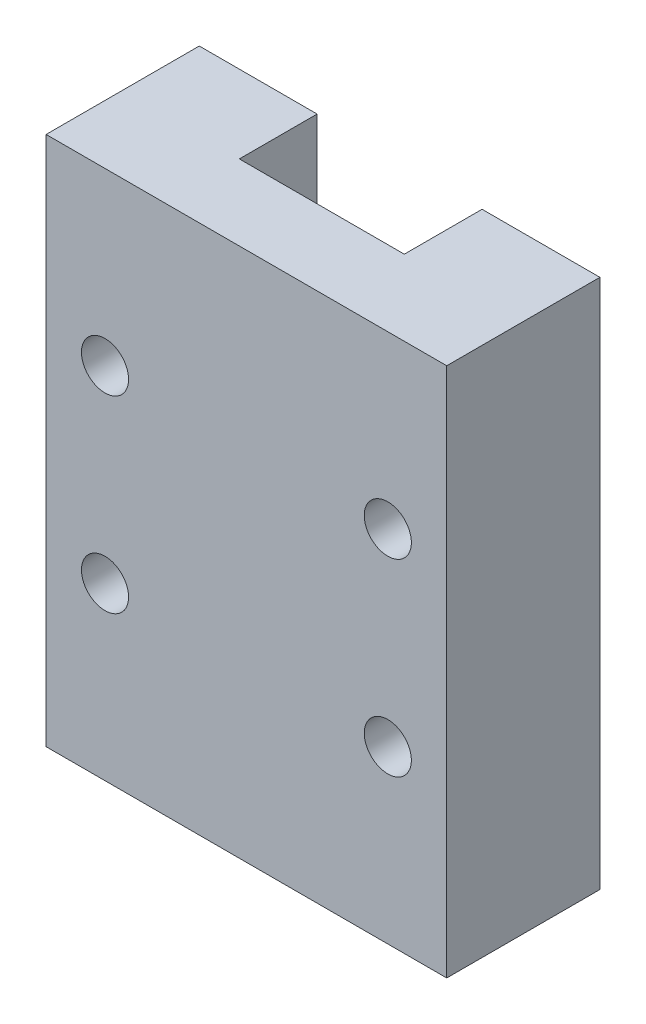
SolidWorks part; units mm, degrees
ref_plane "Front Plane" through (0, 0, 0) normal (0, 0, 1) x (1, 0, 0)
ref_plane "Top Plane" through (0, 0, 0) normal (0, 1, 0) x (1, 0, 0)
ref_plane "Right Plane" through (0, 0, 0) normal (1, 0, 0) x (0, 0, -1)
sketch "Sketch1" plane through (0, 0, 0) normal (0, 0, 1) x (1, 0, 0)
  line L1 (-8.5, -11.25) -> (8.5, -11.25)
  line L2 (-8.5, -11.25) -> (-8.5, 11.25)
  line L3 (-8.5, 11.25) -> (8.5, 11.25)
  line L4 (8.5, -11.25) -> (8.5, 11.25)
  line L5 (-8.5, -11.25) -> (8.5, 11.25) construction
  line L6 (-8.5, 11.25) -> (8.5, -11.25) construction
  point P0 (0, 0)
  dimension "D1" = 17
  dimension "D2" = 22.5
extrude "Boss-Extrude1" add sketch "Sketch1" against normal blind 6.5
sketch "Sketch2" plane through (0, 0, 0) normal (0, 0, 1) x (1, 0, 0)
  line L1 (-6, -4) -> (6, -4) construction
  line L2 (-6, -4) -> (-6, 4) construction
  line L3 (-6, 4) -> (6, 4) construction
  line L4 (6, -4) -> (6, 4) construction
  line L5 (-6, -4) -> (6, 4) construction
  line L6 (-6, 4) -> (6, -4) construction
  circle A0 centre (6, 4) radius 1
  circle A1 centre (6, -4) radius 1
  circle A2 centre (-6, -4) radius 1
  circle A3 centre (-6, 4) radius 1
  point P0 (0, 0)
  dimension "D3" = 2
  dimension "D4" = 2
  dimension "D5" = 2
  dimension "D6" = 2
  dimension "D1" = 8
  dimension "D2" = 12
extrude "Cut-Extrude1" cut sketch "Sketch2" against normal blind 2.5
sketch "Sketch3" plane through (0, -11.25, 0) normal (0, -1, 0) x (1, 0, 0)
  line L0 (0, 0) -> (0, -6.5) construction
  line L1 (-8.5, -6.5) -> (8.5, -6.5) construction
  line L3 (-3.5, -9.8) -> (3.5, -9.8)
  line L4 (-3.5, -9.8) -> (-3.5, -3.2)
  line L5 (-3.5, -3.2) -> (3.5, -3.2)
  line L6 (3.5, -9.8) -> (3.5, -3.2)
  line L7 (-3.5, -9.8) -> (3.5, -3.2) construction
  line L8 (-3.5, -3.2) -> (3.5, -9.8) construction
  dimension "D1" = 7
  dimension "D2" = 3.3
extrude "Cut-Extrude2" cut sketch "Sketch3" against normal through all
